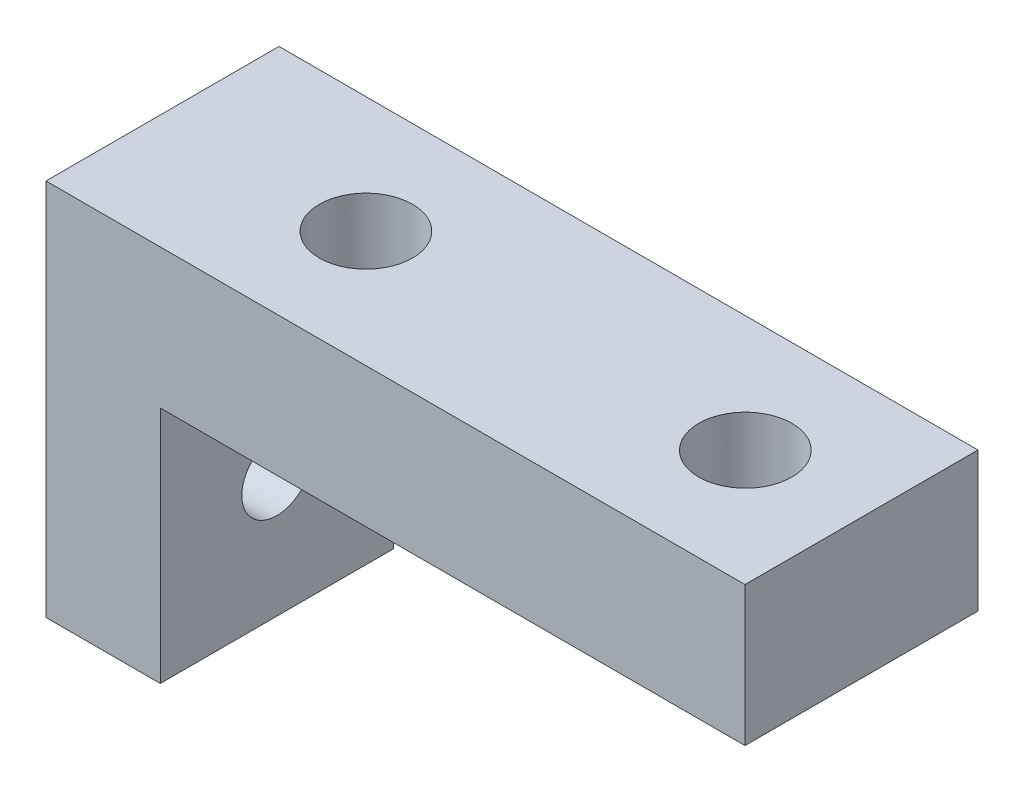
SolidWorks part; units mm, degrees
ref_plane "Front Plane" through (0, 0, 0) normal (0, 0, 1) x (1, 0, 0)
ref_plane "Top Plane" through (0, 0, 0) normal (0, 1, 0) x (1, 0, 0)
ref_plane "Right Plane" through (0, 0, 0) normal (1, 0, 0) x (0, 0, -1)
sketch "Sketch1" plane through (0, 0, 0) normal (0, 0, 1) x (1, 0, 0)
  line L0 (-54.7356, 0) -> (-24.7356, 0)
  line L1 (-24.7356, 0) -> (-24.7356, -5.9856)
  line L2 (-24.7356, -5.9856) -> (-49.8317, -5.9856)
  line L3 (-49.8317, -5.9856) -> (-49.8317, -16.226)
  line L4 (-49.8317, -16.226) -> (-54.7356, -16.226)
  line L5 (-54.7356, -16.226) -> (-54.7356, 0)
  dimension "D1" = 30
extrude "Boss-Extrude1" add sketch "Sketch1" along normal blind 10
sketch "Sketch2" plane through (0, 0, 0) normal (0, 1, 0) x (1, 0, 0)
  line L0 (-54.7356, -5) -> (-29.7215, -5) construction
  line L1 (-54.7356, -10) -> (-54.7356, 0) construction
  line L2 (-24.7356, -10) -> (-54.7356, -10) construction
  line L3 (-24.7356, 0) -> (-54.7356, 0) construction
  arc A0 (-29.5971, -10) -> (-29.5971, 0) centre (-29.7215, -5) ccw
  circle A1 centre (-46.0039, -5) radius 0.9893
ref_plane "Plane1" through (-24.7356, 0, 10) normal (0, 0, -1) x (-1, 0, 0)
sketch "Sketch6" plane through (-24.7356, 0, 10) normal (0, 0, -1) x (-1, 0, 0)
  line L0 (4.8615, 0) -> (4.8615, -5.9856)
  line L1 (25.0962, -5.9856) -> (0, -5.9856) construction
  line L2 (4.8615, -5.9856) -> (0, -5.9856)
  line L3 (0, -5.9856) -> (0, 0)
  line L4 (0, 0) -> (4.8615, 0)
sketch "Sketch7" plane through (0, 0, 0) normal (0, 1, 0) x (1, 0, 0)
  circle A0 centre (-29.7215, -5) radius 0.9918
extrude "Cut-Extrude1" cut sketch "Sketch7" against normal through all both and the other way through all
extrude "Cut-Extrude2" cut sketch "Sketch2" against normal through all both and the other way through all contours L0 A1 | A1 L0
sketch "Sketch9" plane through (-54.7356, 0, 0) normal (-1, 0, 0) x (0, 0, 1)
  line L0 (5, 0) -> (5, -16.226) construction
  line L1 (10, 0) -> (0, 0) construction
  line L2 (10, -16.226) -> (0, -16.226) construction
  circle A0 centre (5, -10.9901) radius 0.9865
extrude "Cut-Extrude3" cut sketch "Sketch9" against normal through all both and the other way through all
sketch "Sketch10" plane through (-54.7356, 0, 0) normal (-1, 0, 0) x (0, 0, 1)
  circle A0 centre (5, -10.9901) radius 1.5
extrude "Cut-Extrude4" cut sketch "Sketch10" against normal through all both and the other way through all
sketch "Sketch12" plane through (0, 0, 0) normal (0, 1, 0) x (1, 0, 0)
  circle A0 centre (-46.0039, -5) radius 2
  circle A1 centre (-29.7215, -5) radius 2
extrude "Cut-Extrude5" cut sketch "Sketch12" against normal through all both and the other way through all
